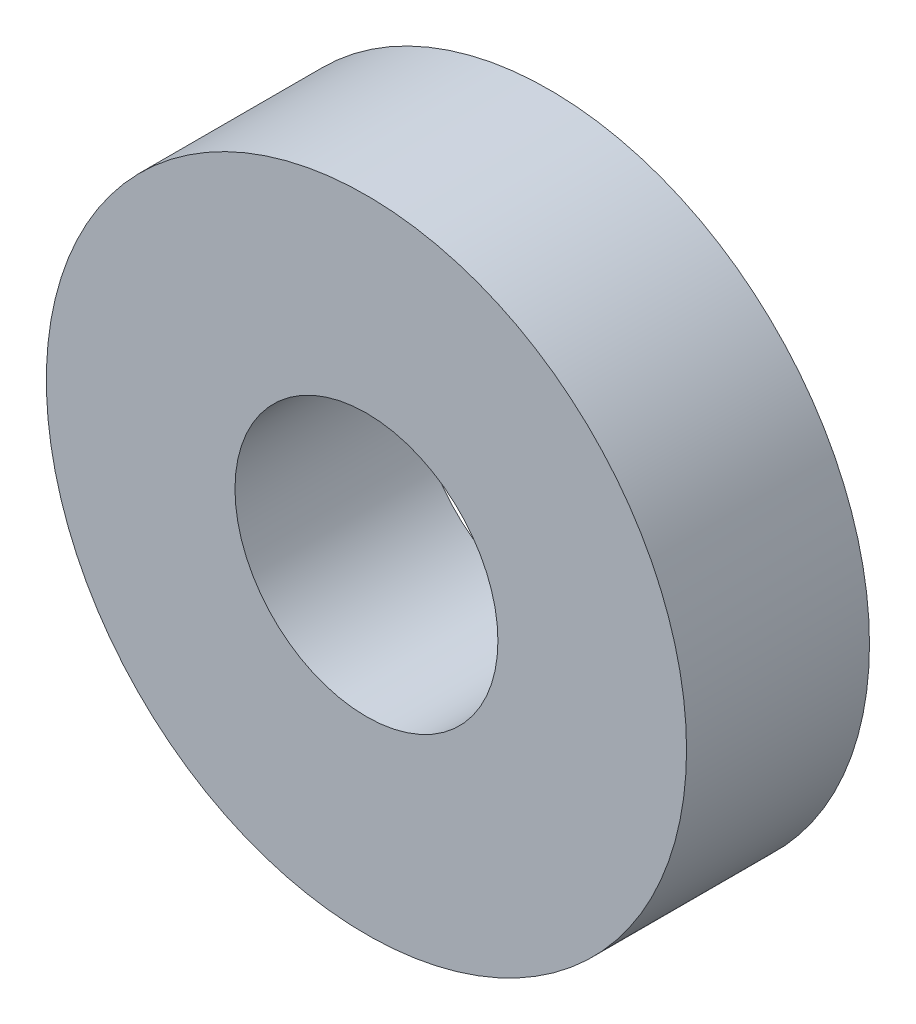
SolidWorks part; units mm, degrees
ref_plane "Alzado" through (0, 0, 0) normal (0, 0, 1) x (1, 0, 0)
ref_plane "Planta" through (0, 0, 0) normal (0, 1, 0) x (1, 0, 0)
ref_plane "Vista lateral" through (0, 0, 0) normal (1, 0, 0) x (0, 0, -1)
sketch "Croquis1" plane through (0, 0, 0) normal (0, 0, 1) x (1, 0, 0)
  circle A0 centre (0, 0) radius 5.75
  circle A1 centre (0, 0) radius 14
  dimension "D1" = 11.5
  dimension "D2" = 28
extrude "Saliente-Extruir1" add sketch "Croquis1" along normal blind 8
sketch "Croquis2" plane through (0, 0, 0) normal (0, 0, -1) x (-1, 0, 0)
  line L1 (14, 14) -> (-14, 14)
  line L2 (14, 14) -> (14, -14)
  line L3 (14, -14) -> (-14, -14)
  line L4 (-14, 14) -> (-14, -14)
  line L5 (14, 14) -> (-14, -14) construction
  line L6 (14, -14) -> (-14, 14) construction
  circle A0 centre (0, 0) radius 14 construction
  point P0 (0, 0)
  point P1 (0, 0)
